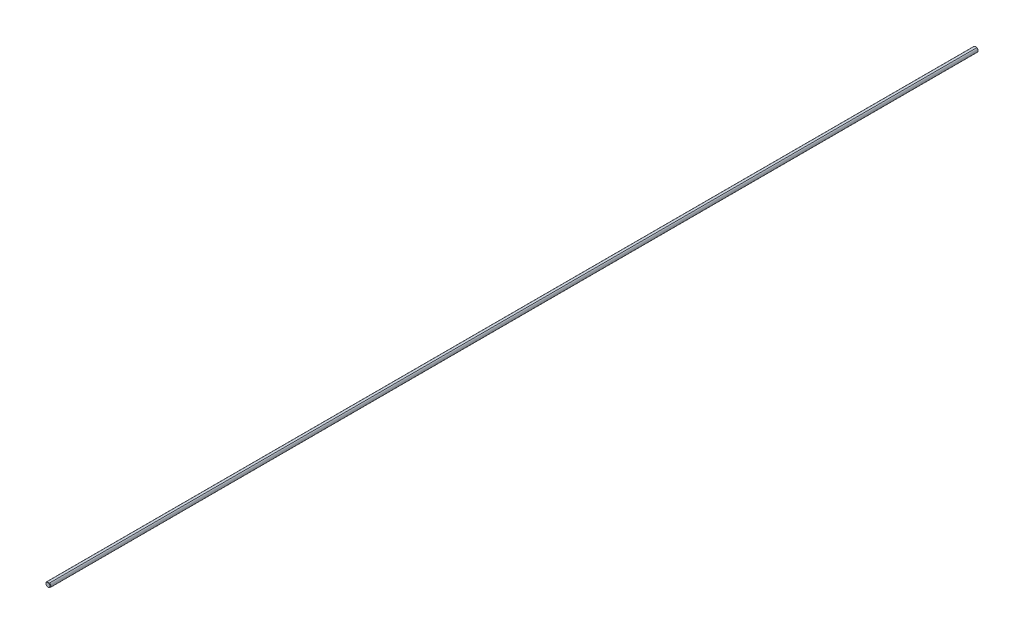
SolidWorks part; units mm, degrees
ref_plane "Front" through (0, 0, 0) normal (0, 0, 1) x (1, 0, 0)
ref_plane "Top" through (0, 0, 0) normal (0, 1, 0) x (1, 0, 0)
ref_plane "Right" through (0, 0, 0) normal (1, 0, 0) x (0, 0, -1)
sketch "Sketch1" plane through (0, 0, 0) normal (0, 0, 1) x (1, 0, 0)
  circle A0 centre (0, 0) radius 3.175
  dimension "D1" = 6.35
extrude "Extrude1" add sketch "Sketch1" along normal mid plane 1219.2
chamfer "Chamfer1" distance 0.635 angle 45 2 edges at (3.175, 0, -609.6) (3.175, 0, 609.6)
sketch "Sketch13" plane through (0, 0, 0) normal (0, 0, 1) x (1, 0, 0)
  line L3 (-1.5875, 2.7496) -> (1.5875, 2.7496)
  circle A0 centre (0, 0) radius 3.175 construction
  arc A1 (1.5875, 2.7496) -> (-1.5875, 2.7496) centre (0, 0) ccw
  dimension "D1" = 3.175
extrude "Extrude7" cut sketch "Sketch13" against normal through all and the other way through all
equation "\"D1@Chamfer1\" = \"D1@Sketch1\" * .1"
equation "\"D1@Sketch13\" = \"D1@Sketch1\" * .5"
